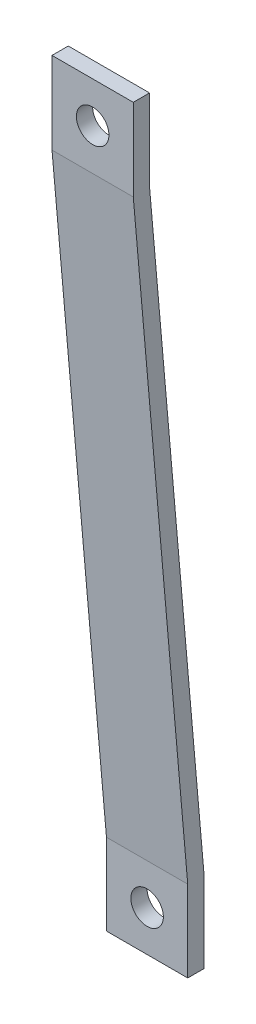
SolidWorks part; units mm, degrees
ref_plane "Front Plane" through (0, 0, 0) normal (0, 0, 1) x (1, 0, 0)
ref_plane "Top Plane" through (0, 0, 0) normal (0, 1, 0) x (1, 0, 0)
ref_plane "Right Plane" through (0, 0, 0) normal (1, 0, 0) x (0, 0, -1)
sketch "Sketch2" plane through (0, 0, 0) normal (1, 0, 0) x (0, 0, -1)
  line L0 (-10.0497, 145) -> (-10.0497, 130)
  line L1 (0, 0) -> (0, 73.757) construction
  line L2 (-10.0497, 130) -> (0, 15.131)
  line L3 (0, 15.131) -> (0, 0)
  line L4 (-13.0497, 145) -> (-13.0497, 129.869)
  line L5 (-13.0497, 129.869) -> (-3, 15)
  line L6 (-3, 15) -> (-3, 0)
  line L7 (-13.0497, 145) -> (-10.0497, 145)
  line L8 (-3, 0) -> (0, 0)
  dimension "D1" = 3
  dimension "D2" = 145
  dimension "D3" = 5
  dimension "D4" = 15
  dimension "D5" = 15
extrude "Boss-Extrude1" add sketch "Sketch2" along normal blind 15
sketch "Sketch3" plane through (0, 0, 3) normal (0, 0, 1) x (1, 0, 0)
  line L1 (0, 15) -> (0, 0) construction
  line L2 (15, 0) -> (0, 0) construction
  circle A0 centre (7.5, 7.5) radius 3
  dimension "D1" = 6
  dimension "D2" = 7.5
  dimension "D3" = 7.5
extrude "Cut-Extrude1" cut sketch "Sketch3" against normal up to surface (3 mm away) contours A0 up to face at (7.5, 7.5655, 0)
sketch "Sketch4" plane through (0, 0, 13.0497) normal (0, 0, 1) x (1, 0, 0)
  line L0 (15, 145) -> (15, 129.869) construction
  line L1 (15, 145) -> (0, 145) construction
  circle A0 centre (7.5, 137.5) radius 3
  dimension "D1" = 6
  dimension "D2" = 7.5
  dimension "D3" = 7.5
extrude "Cut-Extrude2" cut sketch "Sketch4" against normal up to surface (3 mm away) contours A0 up to face at (7.5, 137.5, 10.0497)
equation "\"curvedBarWidth\"=15"
equation "\"D2@Sketch3\"=\"curvedBarWidth\"/2"
